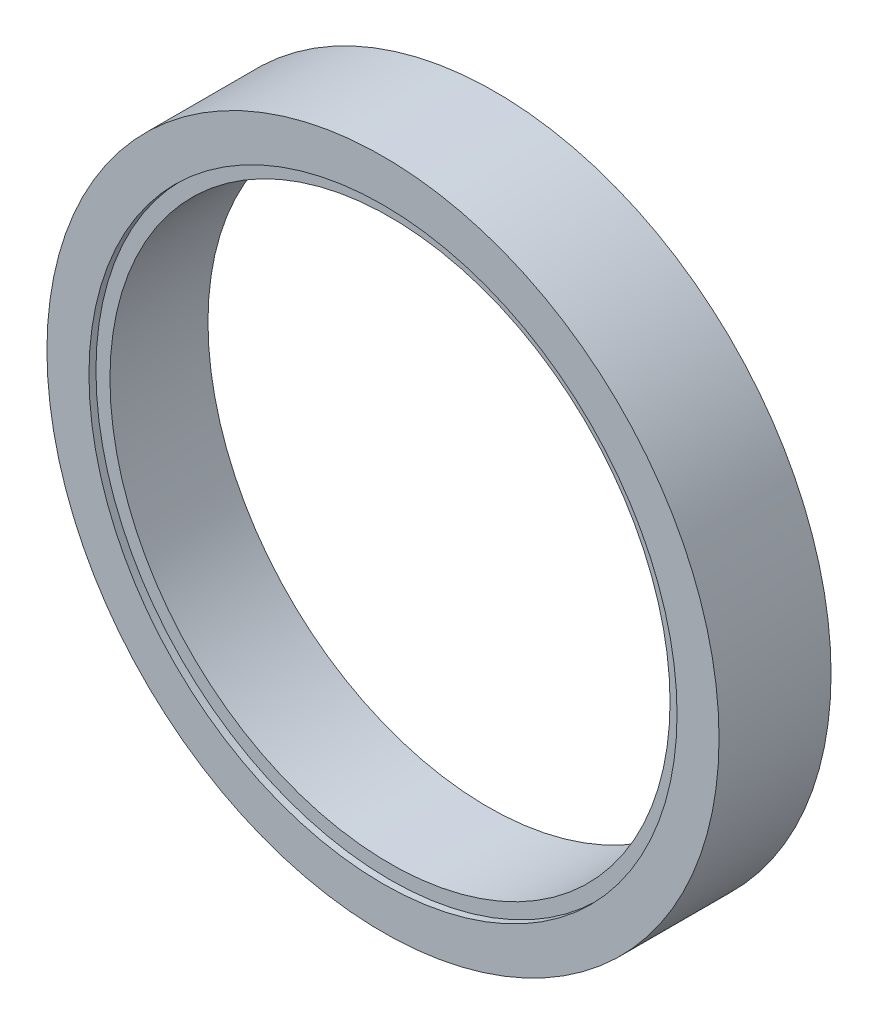
SolidWorks part; units mm, degrees
ref_plane "Front Plane" through (0, 0, 0) normal (0, 0, 1) x (1, 0, 0)
ref_plane "Top Plane" through (0, 0, 0) normal (0, 1, 0) x (1, 0, 0)
ref_plane "Right Plane" through (0, 0, 0) normal (1, 0, 0) x (0, 0, -1)
sketch "Sketch1" plane through (0, 0, 0) normal (0, 0, 1) x (1, 0, 0)
  circle A0 centre (0, 0) radius 76.2
  circle A1 centre (0, 0) radius 63.5
  dimension "D1" = 152.4
  dimension "D2" = 12.7
extrude "Boss-Extrude1" add sketch "Sketch1" along normal mid plane 25.4
sketch "Sketch2" plane through (0, 0, 12.7) normal (0, 0, 1) x (1, 0, 0)
  circle A2 centre (0, 0) radius 66.675
  circle A3 centre (0, 0) radius 66.675
  dimension "D1" = 9.525
extrude "Cut-Extrude1" cut sketch "Sketch2" against normal blind 1.5875
sketch "Sketch3" plane through (0, 0, -12.7) normal (0, 0, -1) x (-1, 0, 0)
  circle A2 centre (0, 0) radius 69.85
  circle A3 centre (0, 0) radius 69.85
  dimension "D1" = 6.35
extrude "Cut-Extrude2" cut sketch "Sketch3" against normal blind 1.5875
